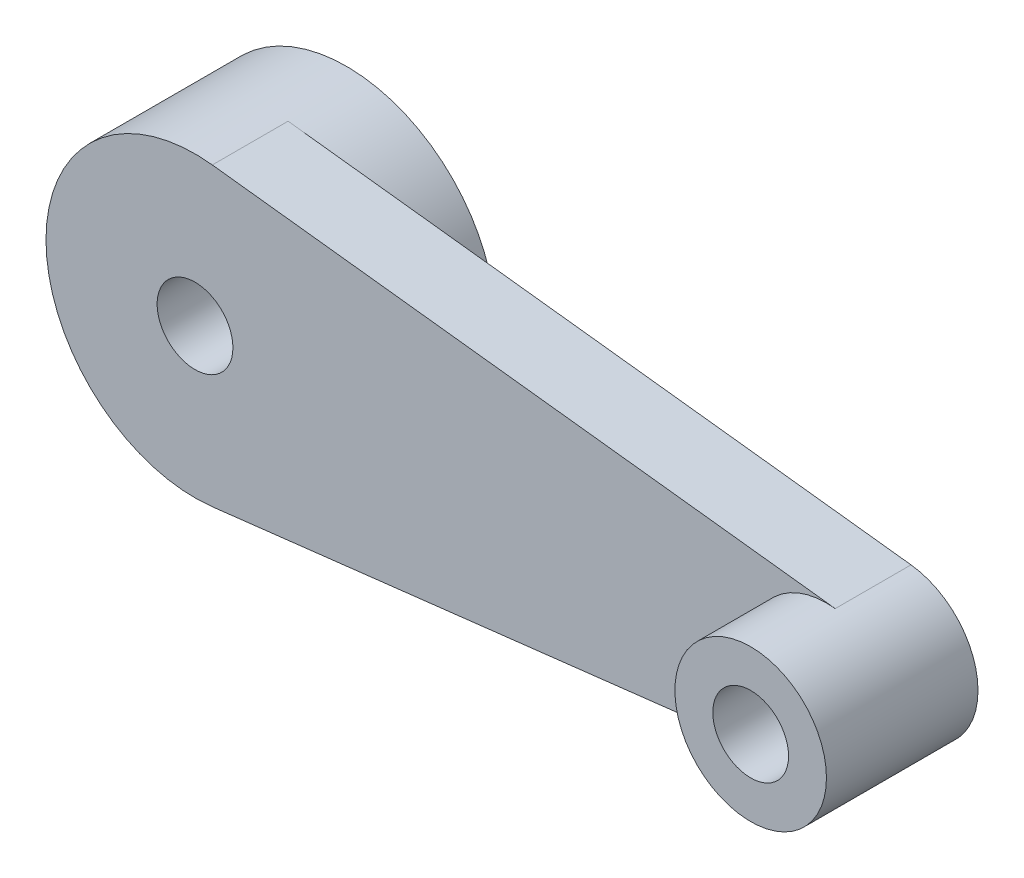
SolidWorks part; units mm, degrees
ref_plane "Alzado" through (0, 0, 0) normal (0, 0, 1) x (1, 0, 0)
ref_plane "Planta" through (0, 0, 0) normal (0, 1, 0) x (1, 0, 0)
ref_plane "Vista lateral" through (0, 0, 0) normal (1, 0, 0) x (0, 0, -1)
sketch "Corte" plane through (0, 0, 0) normal (0, 0, 1) x (1, 0, 0)
  line L0 (35.9291, 45.5052) -> (60.5927, 42.6248)
  line L1 (60.5927, 36.6653) -> (35.9291, 33.7849)
  arc A0 (35.9291, 45.5052) -> (35.9291, 33.7849) centre (35.2447, 39.645) ccw
  arc A1 (60.5927, 36.6653) -> (60.5927, 42.6248) centre (60.2447, 39.645) ccw
  circle A2 centre (35.2447, 39.645) radius 1.5
  circle A3 centre (60.2447, 39.645) radius 1.5
sketch "Ext1" plane through (0, 0, 0) normal (0, 0, 1) x (1, 0, 0)
  circle A0 centre (35.2447, 39.645) radius 5.9
  circle A1 centre (35.2447, 39.645) radius 2.75
sketch "Ext2" plane through (0, 0, 0) normal (0, 0, 1) x (1, 0, 0)
  circle A0 centre (60.2447, 39.645) radius 1.5
  circle A1 centre (60.2447, 39.645) radius 3
extrude "Saliente-Extruir1" add sketch "Corte" along normal blind 3
extrude "Saliente-Extruir2" add sketch "Ext1" against normal blind 3
extrude "Saliente-Extruir3" add sketch "Ext2" along normal blind 6
